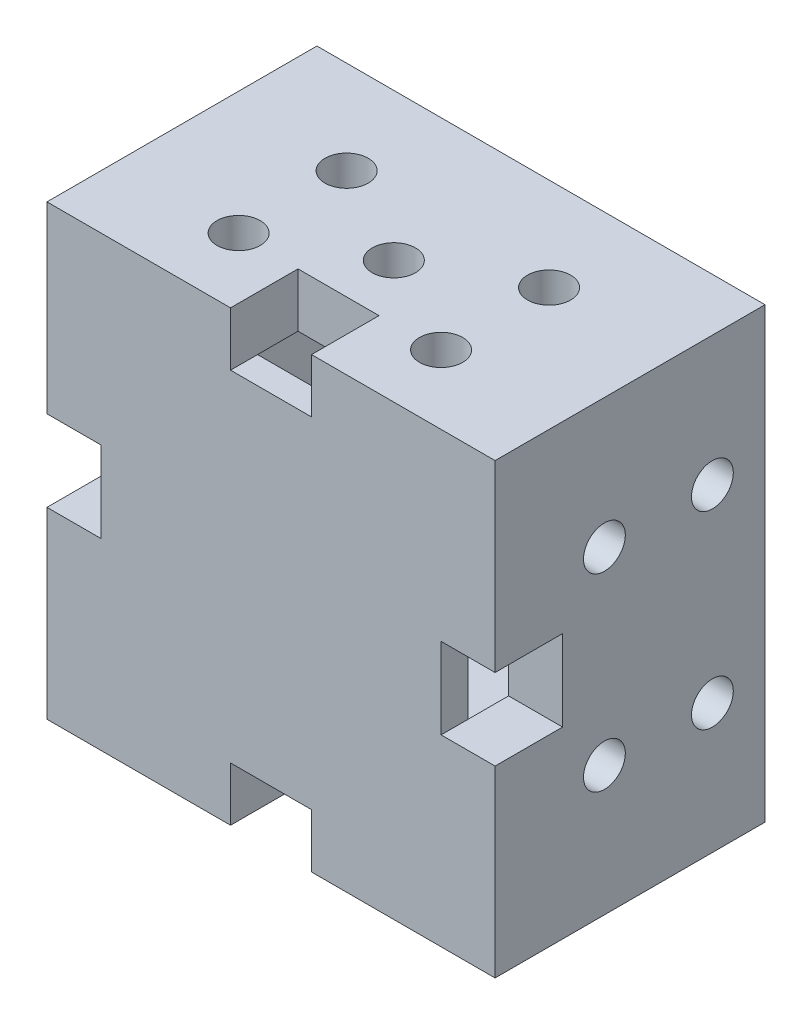
SolidWorks part; units mm, degrees
material "PLA"
ref_plane "前视基准面" through (0, 0, 0) normal (0, 0, 1) x (1, 0, 0)
ref_plane "上视基准面" through (0, 0, 0) normal (0, 1, 0) x (1, 0, 0)
ref_plane "右视基准面" through (0, 0, 0) normal (1, 0, 0) x (0, 0, -1)
sketch "草图1" plane through (0, 0, 0) normal (0, 0, 1) x (1, 0, 0)
  line L1 (12.6, -12.6) -> (-12.6, -12.6)
  line L2 (12.6, -12.6) -> (12.6, 12.6)
  line L3 (12.6, 12.6) -> (-12.6, 12.6)
  line L4 (-12.6, -12.6) -> (-12.6, 12.6)
  line L5 (12.6, -12.6) -> (-12.6, 12.6) construction
  line L6 (12.6, 12.6) -> (-12.6, -12.6) construction
  line L7 (16.6, -16.6) -> (-16.6, -16.6)
  line L8 (16.6, -16.6) -> (16.6, 16.6)
  line L9 (16.6, 16.6) -> (-16.6, 16.6)
  line L10 (-16.6, -16.6) -> (-16.6, 16.6)
  line L11 (16.6, -16.6) -> (-16.6, 16.6) construction
  line L12 (16.6, 16.6) -> (-16.6, -16.6) construction
  circle A0 centre (12.1, 12.6) radius 0.5
  circle A1 centre (-12.1, 12.6) radius 0.5
  circle A2 centre (-12.1, -12.6) radius 0.5
  circle A3 centre (12.1, -12.6) radius 0.5
  point P0 (0, 0)
  point P6 (0, 0)
  dimension "D4" = 1
  dimension "D1" = 25.2
  dimension "D2" = 4
  dimension "D3" = 4
extrude "凸台-拉伸1" add sketch "草图1" along normal blind 18 contours L10 L7 L8 L9 A3 L1 A2 L4 A1 L3 A0 L2
sketch "草图2" plane through (0, 0, 18) normal (0, 0, 1) x (1, 0, 0)
  line L1 (16.6, -16.6) -> (-16.6, -16.6)
  line L2 (16.6, -16.6) -> (16.6, 16.6)
  line L3 (16.6, 16.6) -> (-16.6, 16.6)
  line L4 (-16.6, -16.6) -> (-16.6, 16.6)
  line L5 (16.6, -16.6) -> (-16.6, 16.6) construction
  line L6 (16.6, 16.6) -> (-16.6, -16.6) construction
  point P0 (0, 0)
extrude "凸台-拉伸2" add sketch "草图2" along normal blind 2
sketch "草图3" plane through (-12.6, 0, 0) normal (1, 0, 0) x (0, 0, -1)
  line L0 (-18, -12.6) -> (-18, 12.6) construction
  line L1 (-18, -12.6) -> (-18, 12.6) construction
  line L2 (-16.5, 0) -> (-18, 0) construction
  line L3 (-15, 3) -> (-18, 3)
  line L4 (-15, 3) -> (-15, -3)
  line L5 (-15, -3) -> (-18, -3)
  line L6 (-18, 3) -> (-18, -3)
  line L7 (-15, 3) -> (-18, -3) construction
  line L8 (-15, -3) -> (-18, 3) construction
  point P2 (-16.5, 0)
  dimension "D1" = 3
  dimension "D2" = 6
extrude "切除-拉伸1" cut sketch "草图3" against normal through all and the other way through all
sketch "草图4" plane through (0, 16.6, 0) normal (0, 1, 0) x (1, 0, 0)
  line L0 (11.6, -18) -> (-11.6, -18) construction
  line L1 (11.6, -18) -> (-11.6, -18) construction
  line L2 (0, -16.5) -> (0, -18) construction
  line L3 (-3, -15) -> (3, -15)
  line L4 (-3, -15) -> (-3, -18)
  line L5 (-3, -18) -> (3, -18)
  line L6 (3, -15) -> (3, -18)
  line L7 (-3, -15) -> (3, -18) construction
  line L8 (-3, -18) -> (3, -15) construction
  point P2 (0, -16.5)
  dimension "D1" = 3
  dimension "D2" = 6
extrude "切除-拉伸2" cut sketch "草图4" against normal through all
sketch "草图5" plane through (0, 0, 18) normal (0, 0, -1) x (-1, 0, 0)
  line L0 (-12.6, -3) -> (-16.6, -3) construction
  line L1 (-12.6, 3) -> (-16.6, 3) construction
  line L2 (3, -16.6) -> (3, -12.6) construction
  line L3 (-3, -16.6) -> (-3, -12.6) construction
  line L4 (16.6, 3) -> (12.6, 3) construction
  line L5 (16.6, -3) -> (12.6, -3) construction
  line L6 (-12.6, -3) -> (-16.6, -3)
  line L7 (-12.6, 3) -> (-16.6, 3)
  line L8 (3, -16.6) -> (3, -12.6)
  line L9 (-3, -16.6) -> (-3, -12.6)
  line L10 (16.6, 3) -> (12.6, 3)
  line L11 (16.6, -3) -> (12.6, -3)
  line L12 (-3, 12.6) -> (-3, 16.6) construction
  line L13 (3, 12.6) -> (3, 16.6) construction
  line L14 (-3, 12.6) -> (-3, 16.6)
  line L15 (3, 12.6) -> (3, 16.6)
  line L16 (3, 16.6) -> (-3, 16.6)
  line L17 (3, 12.6) -> (-3, 12.6)
  line L18 (-12.6, 3) -> (-12.6, -3)
  line L19 (-16.6, -3) -> (-16.6, 3)
  line L20 (16.6, 3) -> (16.6, -3)
  line L21 (12.6, -3) -> (12.6, 3)
  line L22 (3, -12.6) -> (-3, -12.6)
  line L23 (3, -16.6) -> (-3, -16.6)
extrude "切除-拉伸3" cut sketch "草图5" against normal through all
sketch "草图6" plane through (0, 16.6, 0) normal (0, 1, 0) x (1, 0, 0)
  line L0 (3, -18) -> (-3, -18) construction
  line L1 (7.5, -14.9) -> (-7.5, -14.9) construction
  line L2 (7.5, -14.9) -> (7.5, -6.9) construction
  line L3 (7.5, -6.9) -> (-7.5, -6.9) construction
  line L4 (-7.5, -14.9) -> (-7.5, -6.9) construction
  line L5 (7.5, -14.9) -> (-7.5, -6.9) construction
  line L6 (7.5, -6.9) -> (-7.5, -14.9) construction
  circle A0 centre (7.5, -6.9) radius 1.6
  circle A1 centre (7.5, -14.9) radius 1.6
  circle A2 centre (-7.5, -14.9) radius 1.6
  circle A3 centre (-7.5, -6.9) radius 1.6
  circle A4 centre (0, -10.9) radius 1.6
  point P0 (0, -10.9)
  dimension "D4" = 3.2
  dimension "D1" = 15
  dimension "D2" = 3.1
  dimension "D3" = 8
extrude "切除-拉伸4" cut sketch "草图6" against normal through all
sketch "草图7" plane through (16.6, 0, 0) normal (1, 0, 0) x (0, 0, -1)
  line L0 (-18, -3) -> (-18, 3) construction
  line L1 (-11.9, -7) -> (-3.9, -7) construction
  line L2 (-11.9, -7) -> (-11.9, 7) construction
  line L3 (-11.9, 7) -> (-3.9, 7) construction
  line L4 (-3.9, -7) -> (-3.9, 7) construction
  line L5 (-11.9, -7) -> (-3.9, 7) construction
  line L6 (-11.9, 7) -> (-3.9, -7) construction
  circle A0 centre (-3.9, -7) radius 1.55
  circle A1 centre (-11.9, -7) radius 1.55
  circle A2 centre (-11.9, 7) radius 1.55
  circle A3 centre (-3.9, 7) radius 1.55
  point P0 (-7.9, 0)
  dimension "D1" = 3.1
  dimension "D2" = 8
  dimension "D3" = 14
  dimension "D4" = 6.1
extrude "切除-拉伸5" cut sketch "草图7" against normal through all
